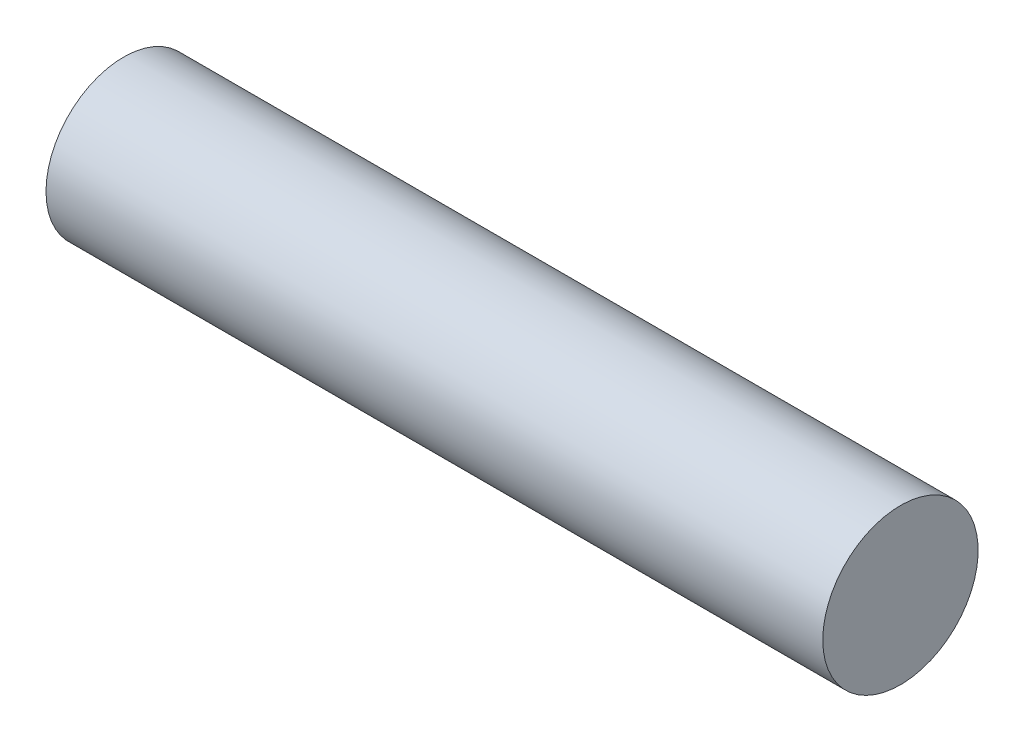
SolidWorks part; units mm, degrees
ref_plane "Front Plane" through (0, 0, 0) normal (0, 0, 1) x (1, 0, 0)
ref_plane "Top Plane" through (0, 0, 0) normal (0, 1, 0) x (1, 0, 0)
ref_plane "Right Plane" through (0, 0, 0) normal (1, 0, 0) x (0, 0, -1)
sketch "Sketch1" plane through (0, 0, 0) normal (0, 1, 0) x (1, 0, 0)
  line L1 (-100, -0.4108) -> (100, -0.4108)
  line L2 (-100, -0.4108) -> (-100, 19.5892)
  line L3 (-100, 19.5892) -> (100, 19.5892)
  line L4 (100, -0.4108) -> (100, 19.5892)
  dimension "D1" = 200
  dimension "D2" = 20
  dimension "D3" = 100
revolve "Revolve1" add sketch "Sketch1" angle 360 about L1
